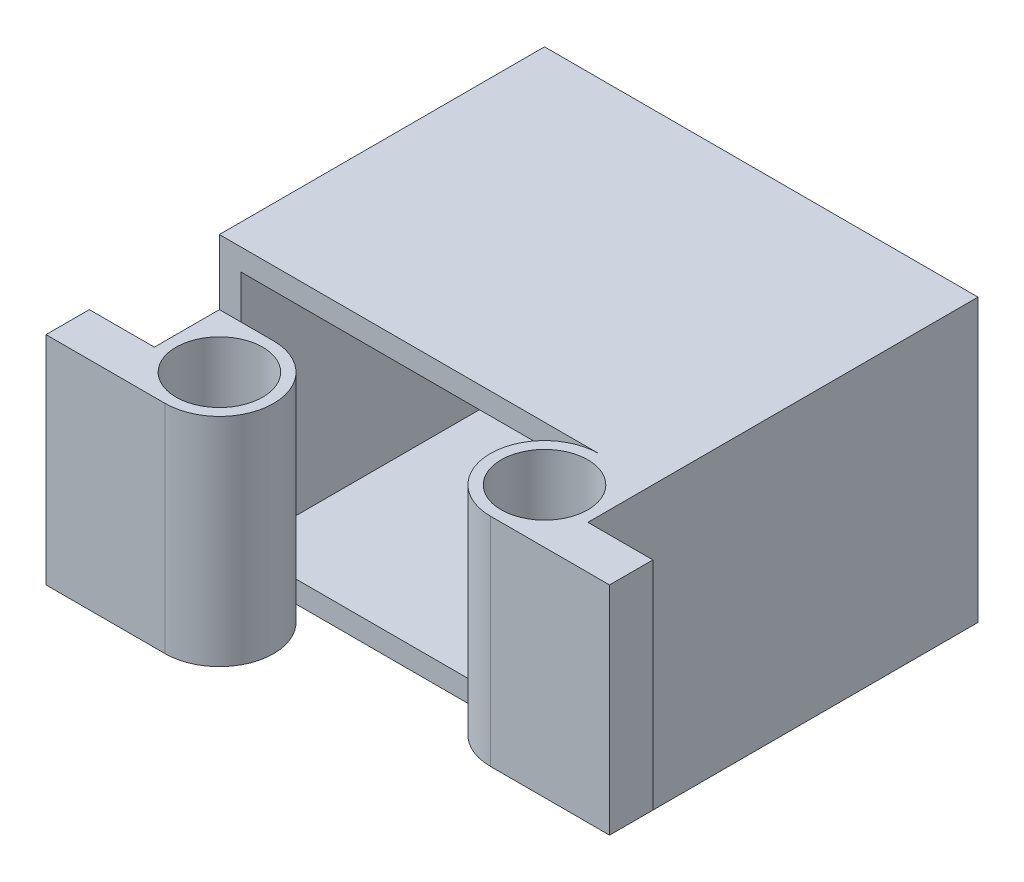
SolidWorks part; units mm, degrees
ref_plane "정면" through (0, 0, 0) normal (0, 0, 1) x (1, 0, 0)
ref_plane "윗면" through (0, 0, 0) normal (0, 1, 0) x (1, 0, 0)
ref_plane "우측면" through (0, 0, 0) normal (1, 0, 0) x (0, 0, -1)
sketch "스케치1" plane through (0, 0, 0) normal (0, 0, 1) x (1, 0, 0)
  line L1 (-10, -6.5) -> (10, -6.5)
  line L2 (-10, -6.5) -> (-10, 6.5)
  line L3 (-10, 6.5) -> (10, 6.5)
  line L4 (10, -6.5) -> (10, 6.5)
  line L5 (-10, -6.5) -> (10, 6.5) construction
  line L6 (-10, 6.5) -> (10, -6.5) construction
  point P0 (0, 0)
  dimension "D1" = 13
  dimension "D2" = 20
extrude "보스-돌출1" add sketch "스케치1" along normal blind 15
shell "쉘1" thickness 1
ref_plane "평면1" through (0, 3.5, 0) normal (0, 1, 0) x (1, 0, 0)
sketch "스케치2" plane through (0, 3.5, 0) normal (0, 1, 0) x (1, 0, 0)
  line L0 (10, -15) -> (-10, -15) construction
  line L2 (-10, -15) -> (-10, 0) construction
  line L3 (-10, -15) -> (-10, -17.5)
  line L5 (-10, -17.5) -> (-10, -20)
  line L6 (-10, -20) -> (-7.5, -20)
  line L9 (-10, -15) -> (-7.5, -15)
  circle A0 centre (-7.5, -17.5) radius 2.5
  circle A2 centre (-7.5, -17.5) radius 2
  dimension "D2" = 5
  dimension "D3" = 4
extrude "보스-돌출4" add sketch "스케치2" against normal blind 10 separate body contours A0 L5 L6 | A0 A2 | A0 L9 L3
sketch "스케치3" plane through (0, 0, 1) normal (0, 0, 1) x (1, 0, 0)
  circle A0 centre (0, 0) radius 4.9
  dimension "D1" = 9.8
extrude "컷-돌출1" cut sketch "스케치3" against normal blind 0.2
sketch "스케치9" plane through (0, 6.5, 0) normal (0, 1, 0) x (1, 0, 0)
  line L0 (10, -15) -> (10, -17.5)
  line L1 (7.5, -20) -> (10, -20)
  line L2 (10, -20) -> (10, -17.5)
  line L3 (10, -15) -> (7.5, -15)
  circle A0 centre (7.5, -17.5) radius 2.5
  circle A1 centre (7.5, -17.5) radius 2
  line M3 (-10, -15) -> (10, -15)
  dimension "D1" = 5
  dimension "D2" = 4
extrude "보스-돌출8" add sketch "스케치9" against normal blind 10 contours A0 L0 M3 | A0 L1 L2 | A0 A1
sketch "스케치6" plane through (-10, 0, 0) normal (-1, 0, 0) x (0, 0, 1)
  line L0 (15, -6.5) -> (20, -6.5) construction
  line L1 (20, 3.5) -> (18, 3.5)
  line L2 (20, 3.5) -> (20, -6.5)
  line L3 (20, -6.5) -> (18, -6.5)
  line L4 (18, 3.5) -> (18, -6.5)
  line L6 (15, -6.5) -> (20, -6.5) construction
  line L7 (20, -6.5) -> (20, 3.5) construction
  line L8 (15, 3.5) -> (20, 3.5) construction
  dimension "D1" = 2
extrude "보스-돌출10" add sketch "스케치6" along normal blind 3
sketch "스케치10" plane through (10, 0, 0) normal (1, 0, 0) x (0, 0, -1)
  line L0 (-15, -3.5) -> (-20, -3.5) construction
  line L1 (-20, 6.5) -> (-18, 6.5)
  line L2 (-20, 6.5) -> (-20, -3.5)
  line L3 (-20, -3.5) -> (-18, -3.5)
  line L4 (-18, 6.5) -> (-18, -3.5)
  dimension "D1" = 2
extrude "보스-돌출11" add sketch "스케치10" along normal blind 3
